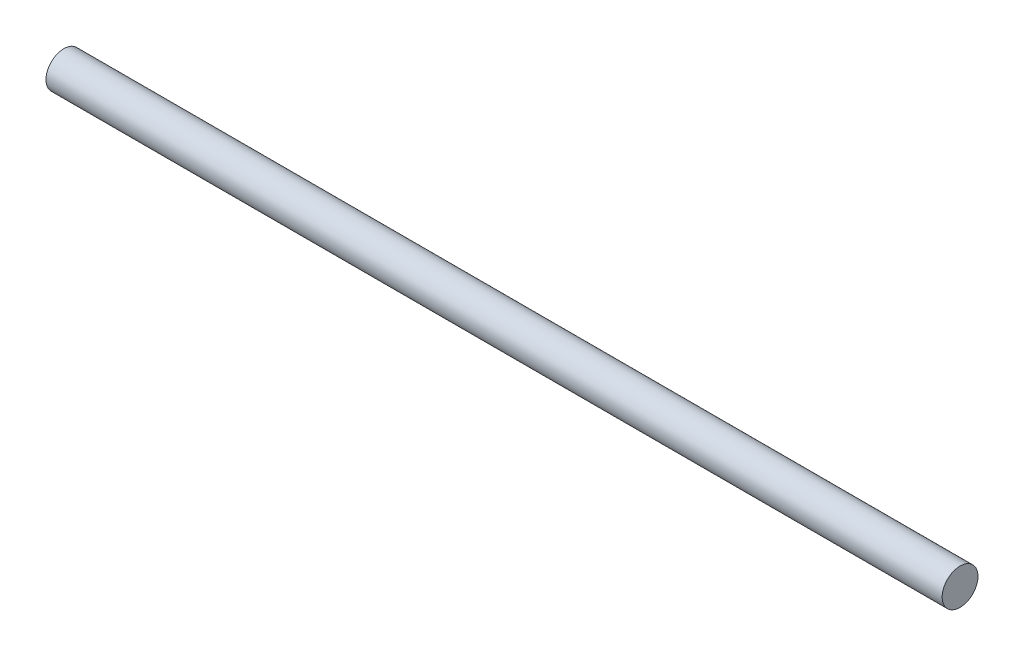
SolidWorks part; units mm, degrees
ref_plane "前视基准面" through (0, 0, 0) normal (0, 0, 1) x (1, 0, 0)
ref_plane "上视基准面" through (0, 0, 0) normal (0, 1, 0) x (1, 0, 0)
ref_plane "右视基准面" through (0, 0, 0) normal (1, 0, 0) x (0, 0, -1)
other "Configuration Table"
sketch "草图1" plane through (0, 0, 0) normal (1, 0, 0) x (0, 0, -1)
  circle A0 centre (0, 0) radius 2
  dimension "D1" = 4
extrude "凸台-拉伸1" add sketch "草图1" along normal blind 100
